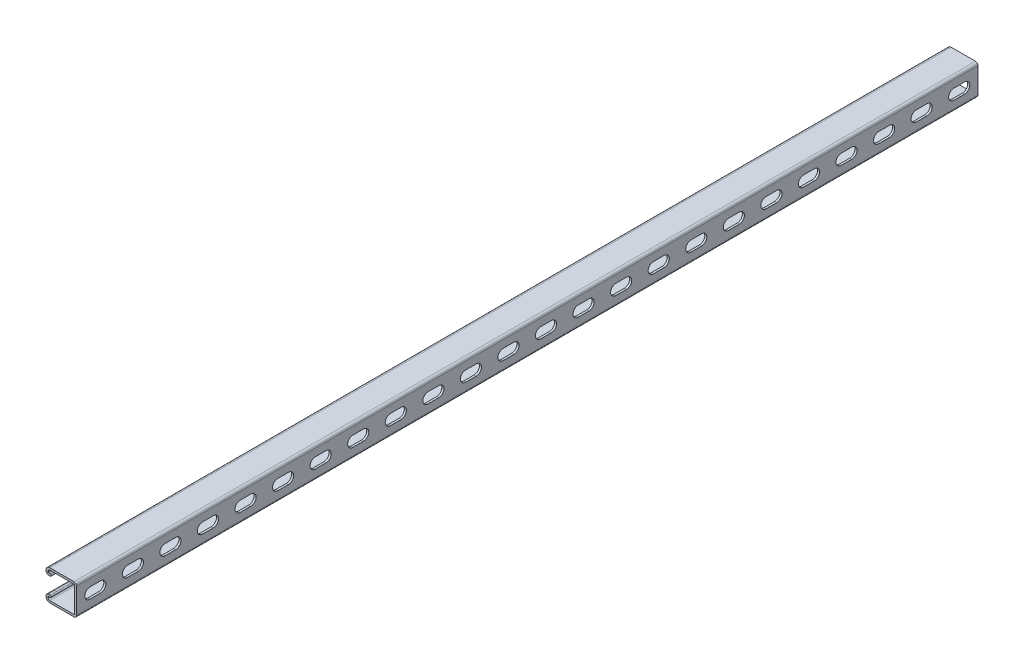
SolidWorks part; units mm, degrees
material "Galvanized Steel"
ref_plane "Front Plane" through (0, 0, 0) normal (0, 0, 1) x (1, 0, 0)
ref_plane "Top Plane" through (0, 0, 0) normal (0, 1, 0) x (1, 0, 0)
ref_plane "Right Plane" through (0, 0, 0) normal (1, 0, 0) x (0, 0, -1)
sketch "Sketch1" plane through (0, 0, 0) normal (0, 0, 1) x (1, 0, 0)
  line L0 (0, 0) -> (-41.275, 0) construction
  line L3 (-41.275, 20.6375) -> (0, 20.6375) construction
  line L4 (-41.275, 20.6375) -> (-41.275, -20.6375) construction
  line L5 (-41.275, -20.6375) -> (0, -20.6375) construction
  line L6 (0, 20.6375) -> (0, -20.6375) construction
  line L7 (-36.2267, 20.6375) -> (-3.4607, 20.6375)
  line L8 (0, 17.1767) -> (0, -17.1767)
  line L9 (-2.794, -17.1767) -> (-2.794, 17.1767)
  line L10 (-3.4608, 17.8435) -> (-36.2267, 17.8435)
  line L11 (-41.275, 15.5892) -> (-41.275, 14.5732)
  line L12 (-37.8142, 11.1125) -> (-35.5346, 11.1125)
  line L14 (-35.5346, 13.9065) -> (-37.8142, 13.9065)
  line L15 (-38.481, 14.5732) -> (-38.481, 15.5892)
  line L16 (-38.481, -14.5733) -> (-38.481, -15.5893)
  line L17 (-35.5346, -13.9065) -> (-37.8142, -13.9065)
  line L18 (-37.8142, -11.1125) -> (-35.5346, -11.1125)
  line L19 (-41.275, -15.5893) -> (-41.275, -14.5733)
  line L20 (-3.4607, -17.8435) -> (-36.2267, -17.8435)
  line L21 (-36.2267, -20.6375) -> (-3.4607, -20.6375)
  line L22 (-2.794, -20.6375) -> (-2.794, 20.6375) construction
  arc A1 (0, 17.1767) -> (-3.4607, 20.6375) centre (-3.4607, 17.1767) ccw
  arc A2 (-2.794, 17.1767) -> (-3.4608, 17.8435) centre (-3.4607, 17.1767) ccw
  arc A4 (-36.2267, 20.6375) -> (-41.275, 15.5892) centre (-36.2267, 15.5892) ccw
  arc A5 (-41.275, 14.5732) -> (-37.8142, 11.1125) centre (-37.8142, 14.5732) ccw
  arc A6 (-35.5346, 11.1125) -> (-35.5346, 13.9065) centre (-35.5346, 12.5095) ccw
  arc A7 (-37.8142, 13.9065) -> (-38.481, 14.5732) centre (-37.8142, 14.5732) cw
  arc A8 (-38.481, 15.5892) -> (-36.2267, 17.8435) centre (-36.2267, 15.5892) cw
  arc A9 (-38.481, -15.5893) -> (-36.2267, -17.8435) centre (-36.2267, -15.5893) ccw
  arc A10 (-37.8142, -13.9065) -> (-38.481, -14.5733) centre (-37.8142, -14.5733) ccw
  arc A11 (-35.5346, -11.1125) -> (-35.5346, -13.9065) centre (-35.5346, -12.5095) cw
  arc A12 (-41.275, -14.5733) -> (-37.8142, -11.1125) centre (-37.8142, -14.5733) cw
  arc A13 (-36.2267, -20.6375) -> (-41.275, -15.5893) centre (-36.2267, -15.5893) cw
  arc A14 (-2.794, -17.1767) -> (-3.4607, -17.8435) centre (-3.4607, -17.1767) cw
  arc A15 (0, -17.1767) -> (-3.4607, -20.6375) centre (-3.4607, -17.1767) cw
  point P24 (0, 20.6375)
  point P65 (-2.794, 0)
  dimension "D1" = 3.4608
  dimension "D2" = 5.0482
  dimension "D3" = 3.4608
  dimension "Ht." = 41.275
  dimension "Wd." = 41.275
  dimension "Thk." = 2.794
  dimension "D4" = 9.525
  dimension "D5" = 7.1374
extrude "Boss-Extrude1" add sketch "Sketch1" against normal blind 1219.2
sketch "Sketch3" plane through (0, 0, 0) normal (1, 0, 0) x (0, 0, -1)
  line L0 (0, 0) -> (1219.2, 0) construction
  point P2 (101.6, 0)
  point P3 (1117.6, 0)
  dimension "D1" = 101.6
  dimension "D2" = 101.6
  dimension "D3" = 1219.2
sketch "Sketch2" plane through (0, 0, 0) normal (1, 0, 0) x (0, 0, -1)
  line L0 (18.2562, 0) -> (32.5437, 0) construction
  line L1 (18.2562, 7.1437) -> (32.5437, 7.1437)
  line L2 (18.2562, -7.1437) -> (32.5437, -7.1437)
  line L3 (18.2562, 0) -> (0, 0) construction
  line L4 (25.4, 0) -> (76.2, 0) construction
  line L5 (0, -17.1767) -> (0, 17.1767) construction
  arc A0 (18.2562, 7.1437) -> (18.2562, -7.1437) centre (18.2562, 0) ccw
  arc A1 (32.5437, -7.1437) -> (32.5437, 7.1437) centre (32.5437, 0) ccw
  point P3 (25.4, 0)
  dimension "Hole to End" = 11.1125
  dimension "D2" = 25.4
extrude "Cut-Extrude1" cut sketch "Sketch2" against normal up to vertex (2.794 mm away) up to point (-2.794, 0, 0)
pattern_linear "LPattern1" count 24 spacing 50.8 along (0, 0, -1) of "Cut-Extrude1"
equation "\"D1@LPattern1\" = \"Slot Ctr.@Sketch2\""
equation "\"Hole Count@LPattern1\" = \"Lg.@Boss-Extrude1\" / \"D1@LPattern1\""
equation "\"D3@Sketch3\" = \"Lg.@Boss-Extrude1\""
